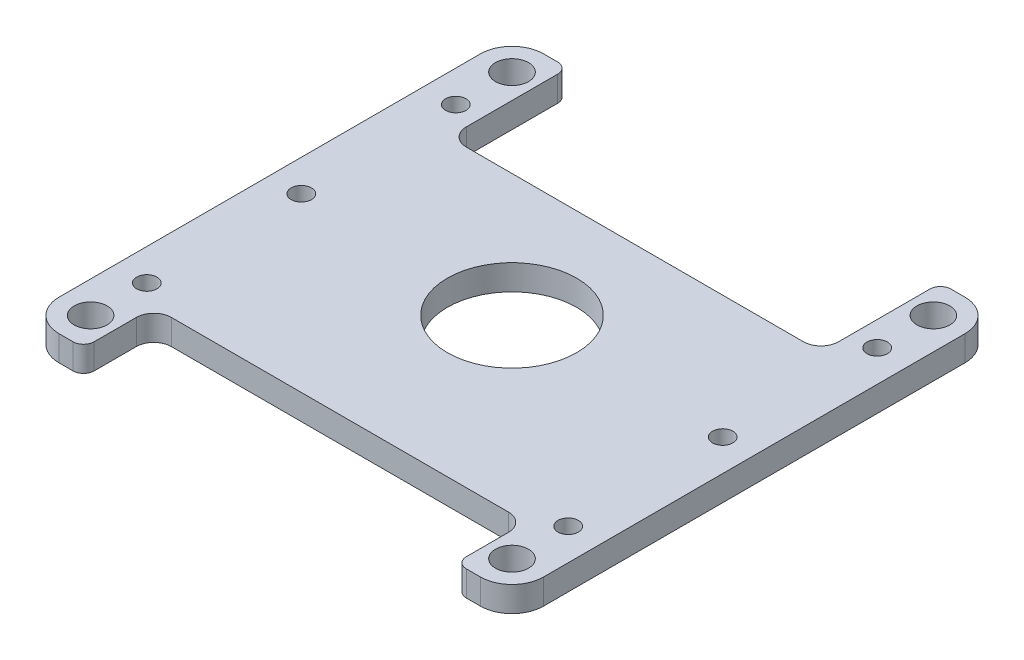
SolidWorks part; units mm, degrees
ref_plane "Front Plane" through (0, 0, 0) normal (0, 0, 1) x (1, 0, 0)
ref_plane "Top Plane" through (0, 0, 0) normal (0, 1, 0) x (1, 0, 0)
ref_plane "Right Plane" through (0, 0, 0) normal (1, 0, 0) x (0, 0, -1)
sketch "Sketch1" plane through (0, 0, 0) normal (0, 1, 0) x (1, 0, 0)
  line L1 (35, -35) -> (-35, -35)
  line L2 (35, -35) -> (35, 35)
  line L3 (35, 35) -> (-35, 35)
  line L4 (-35, -35) -> (-35, 35)
  line L5 (35, -35) -> (-35, 35) construction
  line L6 (35, 35) -> (-35, -35) construction
  point P0 (0, 0)
  dimension "D1" = 70
  dimension "D2" = 70
extrude "Boss-Extrude1" add sketch "Sketch1" along normal blind 3.6
sketch "Sketch2" plane through (0, 3.6, 0) normal (0, 1, 0) x (1, 0, 0)
  line L12 (30, 34.5) -> (28, 34.5)
  line L13 (26.5, 33) -> (26.5, 20)
  line L14 (24, 17.5) -> (-24, 17.5)
  line L15 (-26.5, 20) -> (-26.5, 33)
  line L16 (-28, 34.5) -> (-30, 34.5)
  line L17 (-34.5, 30) -> (-34.5, -30)
  line L18 (-30, -34.5) -> (-28, -34.5)
  line L19 (-26.5, -33) -> (-26.5, -27)
  line L20 (-24, -24.5) -> (24, -24.5)
  line L21 (26.5, -27) -> (26.5, -33)
  line L22 (28, -34.5) -> (30, -34.5)
  line L23 (34.5, -30) -> (34.5, 30)
  line L25 (43.8841, -42.8582) -> (-43.8841, -42.8582)
  line L26 (43.8841, -42.8582) -> (43.8841, 42.8582)
  line L27 (43.8841, 42.8582) -> (-43.8841, 42.8582)
  line L28 (-43.8841, -42.8582) -> (-43.8841, 42.8582)
  line L29 (43.8841, -42.8582) -> (-43.8841, 42.8582) construction
  line L30 (43.8841, 42.8582) -> (-43.8841, -42.8582) construction
  arc A12 (28, 34.5) -> (26.5, 33) centre (28, 33) ccw
  arc A13 (24, 17.5) -> (26.5, 20) centre (24, 20) ccw
  arc A14 (-26.5, 20) -> (-24, 17.5) centre (-24, 20) ccw
  arc A15 (-26.5, 33) -> (-28, 34.5) centre (-28, 33) ccw
  arc A16 (-30, 34.5) -> (-34.5, 30) centre (-30, 30) ccw
  arc A17 (-34.5, -30) -> (-30, -34.5) centre (-30, -30) ccw
  arc A18 (-28, -34.5) -> (-26.5, -33) centre (-28, -33) ccw
  arc A19 (-24, -24.5) -> (-26.5, -27) centre (-24, -27) ccw
  arc A20 (26.5, -27) -> (24, -24.5) centre (24, -27) ccw
  arc A21 (26.5, -33) -> (28, -34.5) centre (28, -33) ccw
  arc A22 (30, -34.5) -> (34.5, -30) centre (30, -30) ccw
  arc A23 (34.5, 30) -> (30, 34.5) centre (30, 30) ccw
  point P36 (0, 0)
  dimension "D1" = 4.5
  dimension "D2" = 42
  dimension "D4" = 2.5
  dimension "D10" = 1.5
  dimension "D3" = 69
  dimension "D5" = 2.5
  dimension "D6" = 2.5
  dimension "D7" = 13
  dimension "D8" = 48
  dimension "D9" = 60
  dimension "D11" = 8
  dimension "D12" = 8
  dimension "D13" = 10
  dimension "D14" = 17
  dimension "D15" = 8
  dimension "D16" = 8
  dimension "D17" = 17
  dimension "D18" = 10
  dimension "D19" = 34.5
  dimension "D20" = 24.5
extrude "Cut-Extrude1" cut sketch "Sketch2" against normal blind 10
sketch "Sketch4" plane through (0, 0, 0) normal (0, -1, 0) x (1, 0, 0)
  circle A0 centre (30, -30) radius 2.35 construction
  circle A1 centre (30, -22) radius 1.45 construction
  circle A2 centre (30, 0) radius 1.45 construction
  circle A3 centre (30, 22) radius 1.45 construction
  circle A4 centre (30, 30) radius 2.35 construction
  circle A5 centre (30, -30) radius 2.35
  circle A6 centre (30, -22) radius 1.45
  circle A7 centre (30, 0) radius 1.45
  circle A8 centre (30, 22) radius 1.45
  circle A9 centre (30, 30) radius 2.35
  circle A10 centre (-30, -30) radius 2.35 construction
  circle A11 centre (-30, -22) radius 1.45 construction
  circle A12 centre (0, 0) radius 9.2 construction
  circle A13 centre (-30, 0) radius 1.45 construction
  circle A14 centre (-30, 22) radius 1.45 construction
  circle A15 centre (-30, 30) radius 2.35 construction
  circle A16 centre (-30, -30) radius 2.35
  circle A17 centre (-30, -22) radius 1.45
  circle A18 centre (0, 0) radius 9.2
  circle A19 centre (-30, 0) radius 1.45
  circle A20 centre (-30, 22) radius 1.45
  circle A21 centre (-30, 30) radius 2.35
extrude "Cut-Extrude2" cut sketch "Sketch4" against normal blind 10
